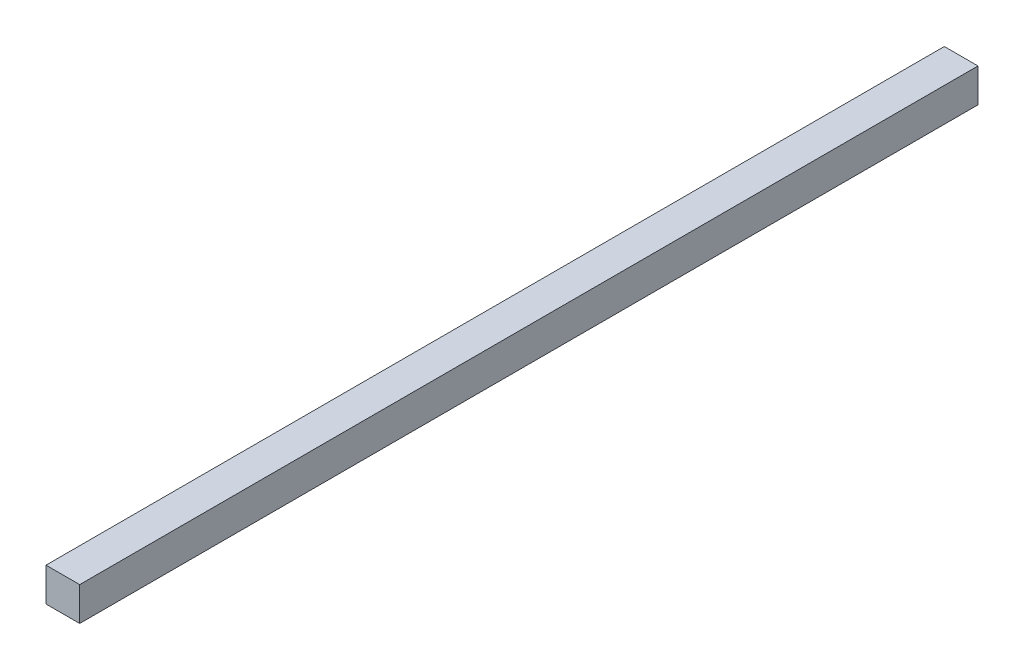
SolidWorks part; units mm, degrees
ref_plane "前视基准面" through (0, 0, 0) normal (0, 0, 1) x (1, 0, 0)
ref_plane "上视基准面" through (0, 0, 0) normal (0, 1, 0) x (1, 0, 0)
ref_plane "右视基准面" through (0, 0, 0) normal (1, 0, 0) x (0, 0, -1)
sketch "草图1" plane through (0, 0, 0) normal (0, 0, 1) x (1, 0, 0)
  line L1 (-7.5, -7.5) -> (7.5, -7.5)
  line L2 (-7.5, -7.5) -> (-7.5, 7.5)
  line L3 (-7.5, 7.5) -> (7.5, 7.5)
  line L4 (7.5, -7.5) -> (7.5, 7.5)
  line L5 (-7.5, -7.5) -> (7.5, 7.5) construction
  line L6 (-7.5, 7.5) -> (7.5, -7.5) construction
  point P0 (0, 0)
  dimension "D1" = 15
  dimension "D2" = 15
extrude "凸台-拉伸1" add sketch "草图1" along normal blind 400
